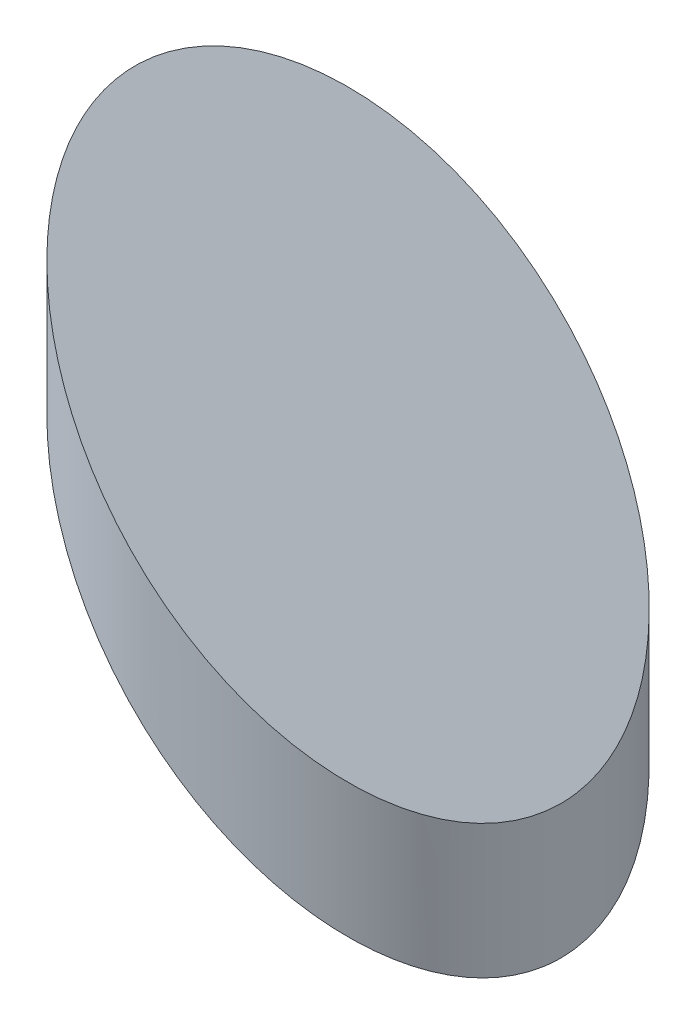
SolidWorks part; units mm, degrees
material "Verre"
ref_plane "Plan de face" through (0, 0, 0) normal (0, 0, 1) x (1, 0, 0)
ref_plane "Plan de dessus" through (0, 0, 0) normal (0, 1, 0) x (1, 0, 0)
ref_plane "Plan de droite" through (0, 0, 0) normal (1, 0, 0) x (0, 0, -1)
sketch "Esquisse1" plane through (0, 0, 0) normal (0, 1, 0) x (1, 0, 0)
  circle A0 centre (0, 0) radius 45
  dimension "D1" = 90
extrude "Boss.-Extru.1" add sketch "Esquisse1" along normal blind 120
sketch "Esquisse2" plane through (0, 0, 0) normal (0, 0, 1) x (1, 0, 0)
  line L0 (45, 0) -> (-45, 90)
  line L1 (-45, 120) -> (-45, 0) construction
  line L2 (-45, 90) -> (-45, 0)
  line L3 (-45, 0) -> (45, 0)
  line L4 (-45, 118.2843) -> (45, 28.2843)
  line L5 (45, 28.2843) -> (45, 120)
  line L6 (45, 120) -> (-45, 120)
  line L7 (-45, 120) -> (-45, 118.2843)
  dimension "D1" = 45
  dimension "D2" = 20
  dimension "D3" = 127.2792
extrude "Enlèv. mat.-Extru.1" cut sketch "Esquisse2" against normal mid plane 120
sketch "Esquisse3" plane through (22.5, 22.5, 0) normal (-0.7071, -0.7071, 0) x (0, 0, 1)
  line L0 (0, 95.4594) -> (0, -31.8198) construction
  line L1 (0, 31.8198) -> (-45, 31.8198) construction
  line L2 (0, 31.8198) -> (45, 31.8198) construction
  ellipse E0 centre (0, 31.8198) end of major axis (0, -31.8198) minor radius 45 construction
sketch "Esquisse4" plane through (36.6421, 36.6421, 0) normal (0.7071, 0.7071, 0) x (0, 0, -1)
  line L0 (0, 115.4594) -> (0, -11.8198) construction
  line L1 (-45, 51.8198) -> (45, 51.8198) construction
  ellipse E0 centre (0, 51.8198) end of major axis (0, -11.8198) minor radius 45 construction
sketch "Esquisse5" plane through (0, 0, 0) normal (0, 0, 1) x (1, 0, 0)
  line L0 (0, 73.2843) -> (0, 75.2843) construction
  line L1 (-45, 118.2843) -> (45, 28.2843) construction
  dimension "D1" = 2
